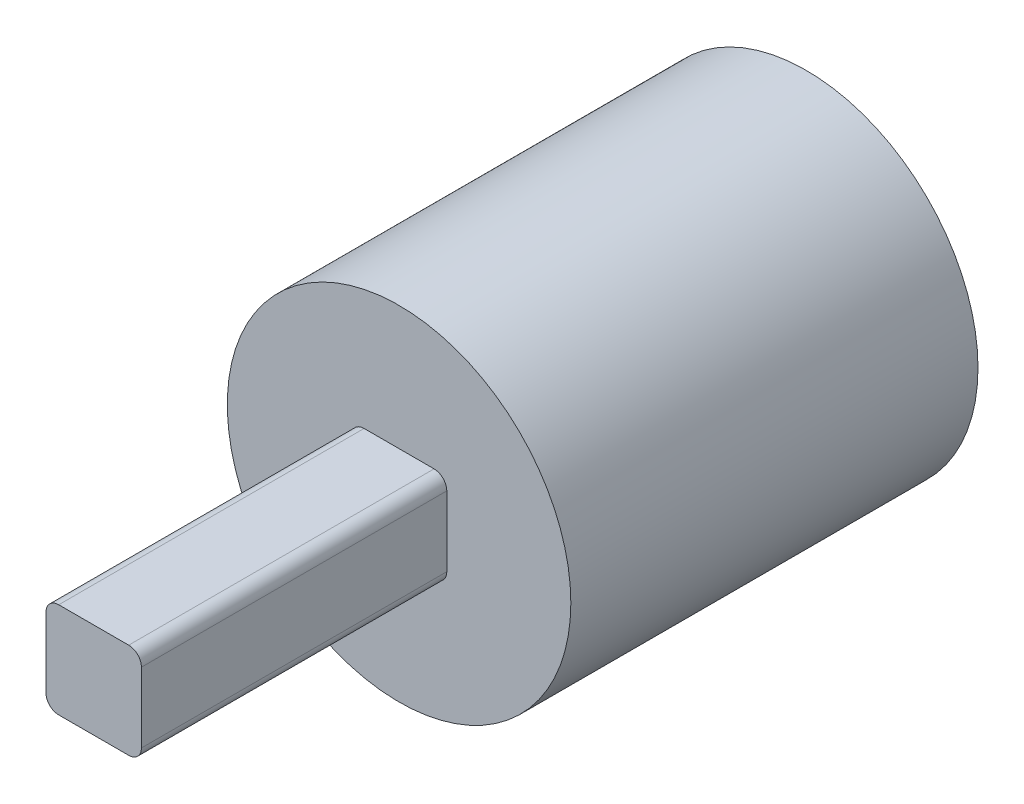
SolidWorks part; units mm, degrees
ref_plane "Front Plane" through (0, 0, 0) normal (0, 0, 1) x (1, 0, 0)
ref_plane "Top Plane" through (0, 0, 0) normal (0, 1, 0) x (1, 0, 0)
ref_plane "Right Plane" through (0, 0, 0) normal (1, 0, 0) x (0, 0, -1)
sketch "Sketch1" plane through (0, 0, 0) normal (0, 0, 1) x (1, 0, 0)
  circle A0 centre (0, 0) radius 13.5
  dimension "D1" = 27
extrude "Boss-Extrude1" add sketch "Sketch1" along normal blind 32 contours A0
sketch "Sketch2" plane through (0, 0, 32) normal (0, 0, 1) x (1, 0, 0)
  line L1 (-2.75, -3.75) -> (2.75, -3.75)
  line L2 (-3.75, -2.75) -> (-3.75, 2.75)
  line L3 (-2.75, 3.75) -> (2.75, 3.75)
  line L4 (3.75, -2.75) -> (3.75, 2.75)
  line L5 (-3.75, -3.75) -> (3.75, 3.75) construction
  line L6 (-3.75, 3.75) -> (3.75, -3.75) construction
  arc A0 (-2.75, -3.75) -> (-3.75, -2.75) centre (-2.75, -2.75) cw
  arc A1 (2.75, 3.75) -> (3.75, 2.75) centre (2.75, 2.75) cw
  arc A2 (2.75, -3.75) -> (3.75, -2.75) centre (2.75, -2.75) ccw
  arc A3 (-3.75, 2.75) -> (-2.75, 3.75) centre (-2.75, 2.75) cw
  point P0 (0, 0)
  dimension "D3" = 1
  dimension "D4" = 1
  dimension "D1" = 7.5
  dimension "D2" = 7.5
extrude "Boss-Extrude2" add sketch "Sketch2" along normal blind 24
